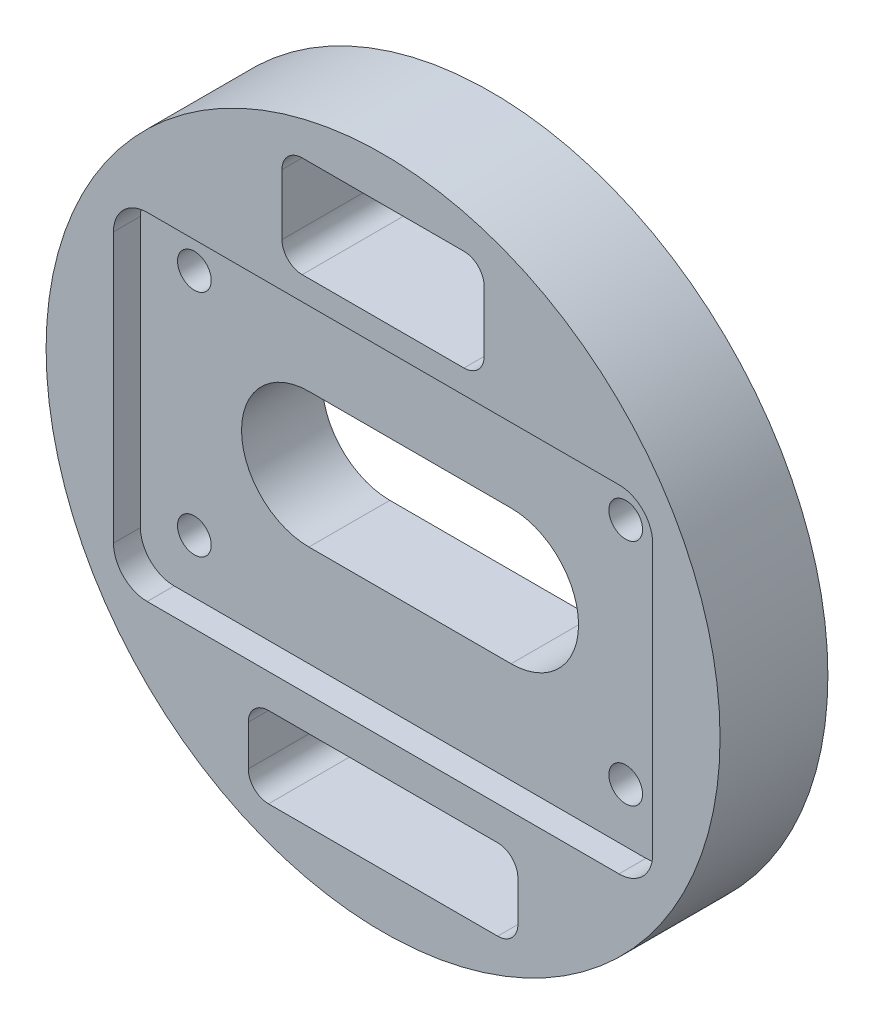
SolidWorks part; units mm, degrees
ref_plane "Front Plane" through (0, 0, 0) normal (0, 0, 1) x (1, 0, 0)
ref_plane "Top Plane" through (0, 0, 0) normal (0, 1, 0) x (1, 0, 0)
ref_plane "Right Plane" through (0, 0, 0) normal (1, 0, 0) x (0, 0, -1)
sketch "Sketch1" plane through (0, 0, 0) normal (0, 0, 1) x (1, 0, 0)
  circle A0 centre (0, 0) radius 25
  dimension "D1" = 50
extrude "Boss-Extrude1" add sketch "Sketch1" against normal blind 8
sketch "Sketch2" plane through (0, 0, 0) normal (0, 0, 1) x (1, 0, 0)
  line L1 (-17.5, 12.5) -> (17.5, 12.5)
  line L2 (-20, 10) -> (-20, -10)
  line L3 (-17.5, -12.5) -> (17.5, -12.5)
  line L4 (20, 10) -> (20, -10)
  line L5 (-20, 12.5) -> (20, -12.5) construction
  line L6 (-20, -12.5) -> (20, 12.5) construction
  arc A0 (17.5, -12.5) -> (20, -10) centre (17.5, -10) ccw
  arc A1 (-20, -10) -> (-17.5, -12.5) centre (-17.5, -10) ccw
  arc A2 (-17.5, 12.5) -> (-20, 10) centre (-17.5, 10) ccw
  arc A3 (17.5, 12.5) -> (20, 10) centre (17.5, 10) cw
  point P0 (0, 0)
  dimension "D3" = 2.5
  dimension "D1" = 40
  dimension "D2" = 25
extrude "Cut-Extrude1" cut sketch "Sketch2" against normal blind 2
sketch "Sketch3" plane through (0, 0, -2) normal (0, 0, 1) x (1, 0, 0)
  line L0 (-7.5, 0) -> (7.5, 0) construction
  line L1 (-7.5, 5) -> (7.5, 5)
  line L2 (-7.5, -5) -> (7.5, -5)
  arc A0 (-7.5, 5) -> (-7.5, -5) centre (-7.5, 0) ccw
  arc A1 (7.5, -5) -> (7.5, 5) centre (7.5, 0) ccw
  point P3 (0, 0)
  dimension "D2" = 5
  dimension "D1" = 15
extrude "Cut-Extrude2" cut sketch "Sketch3" against normal through all
hole_wizard "M3x0.5 Tapped Hole1" positions "Sketch4" profile "Sketch5" tap size "M3x0.5" standard "ANSI Metric" end condition up to next
sketch "Sketch4" plane through (0, 0, -2) normal (0, 0, 1) x (1, 0, 0)
  line L0 (20, -10) -> (20, 10) construction
  line L1 (17.5, 12.5) -> (-17.5, 12.5) construction
  line L2 (0, 0) -> (0, 25) construction
  line L3 (0, 0) -> (25, 0) construction
  circle A0 centre (0, 0) radius 25 construction
  point P0 (16, 8.5)
  point P20 (-16, 8.5)
  point P21 (-16, -8.5)
  point P22 (16, -8.5)
  dimension "D1" = 4
  dimension "D2" = 4
cosmetic thread "Hole Thread1"
cosmetic thread "Hole Thread2"
cosmetic thread "Hole Thread3"
cosmetic thread "Hole Thread4"
sketch "Sketch5" plane through (16, 8.5, -2) normal (1, 0, 0) x (0, -1, 0)
  line L0 (0, 0) -> (0, 6)
  line L1 (0, 6) -> (1.25, 6)
  line L2 (1.25, 6) -> (1.25, 0)
  line L5 (1.25, 0) -> (0, 0)
  line L11 (0, -6.35) -> (0, 107.95) construction
  dimension "Thru Tap Drill Dia." = 2.5
  dimension "Thru Tap Drill Depth" = 6
sketch "Sketch6" plane through (0, 0, 0) normal (0, 0, 1) x (1, 0, 0)
  line L0 (0, 0) -> (0, 25) construction
  line L2 (6, 21.75) -> (-6, 21.75)
  line L3 (7.5, 20.25) -> (7.5, 15.75)
  line L4 (6, 14.25) -> (-6, 14.25)
  line L5 (-7.5, 20.25) -> (-7.5, 15.75)
  line L6 (7.5, 21.75) -> (-7.5, 14.25) construction
  line L7 (7.5, 14.25) -> (-7.5, 21.75) construction
  circle A0 centre (0, 0) radius 25 construction
  arc A1 (7.5, 15.75) -> (6, 14.25) centre (6, 15.75) cw
  arc A2 (-6, 14.25) -> (-7.5, 15.75) centre (-6, 15.75) cw
  arc A3 (-6, 21.75) -> (-7.5, 20.25) centre (-6, 20.25) ccw
  arc A4 (6, 21.75) -> (7.5, 20.25) centre (6, 20.25) cw
  point P6 (0, 18)
  dimension "D4" = 1.5
  dimension "D1" = 18
  dimension "D2" = 15
  dimension "D3" = 7.5
extrude "Cut-Extrude3" cut sketch "Sketch6" against normal through all
sketch "Sketch7" plane through (0, 0, 0) normal (0, 0, 1) x (1, 0, 0)
  line L0 (0, 0) -> (0, -25) construction
  line L2 (-10, -21) -> (10, -21)
  line L3 (-10, -21) -> (-10, -15)
  line L4 (-10, -15) -> (10, -15)
  line L5 (10, -21) -> (10, -15)
  line L6 (-10, -21) -> (10, -15) construction
  line L7 (-10, -15) -> (10, -21) construction
  circle A0 centre (0, 0) radius 25 construction
  point P6 (0, -18)
  dimension "D1" = 6
  dimension "D2" = 20
  dimension "D3" = 18
extrude "Cut-Extrude4" cut sketch "Sketch7" against normal through all
fillet "Fillet1" radius 1.5 4 edges at (10, -21, -4) (-10, -21, -4) (-10, -15, -4) (10, -15, -4)
